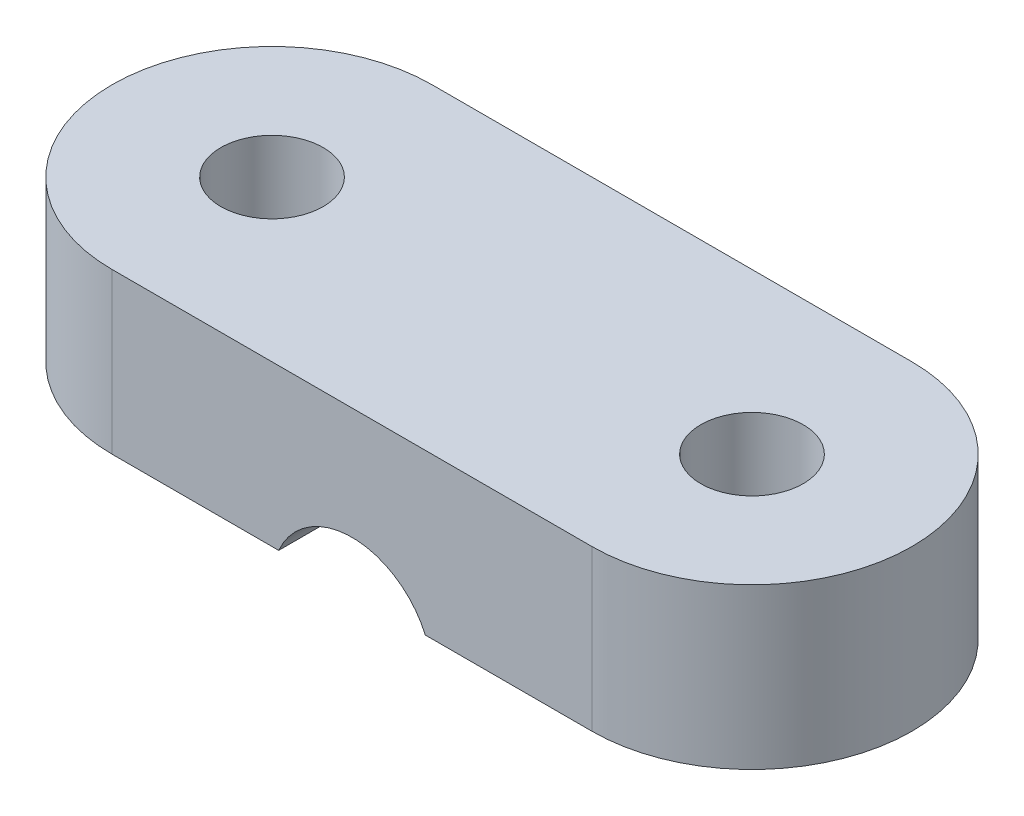
SolidWorks part; units mm, degrees
ref_plane "Front Plane" through (0, 0, 0) normal (0, 0, 1) x (1, 0, 0)
ref_plane "Top Plane" through (0, 0, 0) normal (0, 1, 0) x (1, 0, 0)
ref_plane "Right Plane" through (0, 0, 0) normal (1, 0, 0) x (0, 0, -1)
sketch "Sketch1" plane through (0, 0, 0) normal (0, 1, 0) x (1, 0, 0)
  line L0 (-7.5, 0) -> (7.5, 0) construction
  line L1 (-7.5, 5) -> (7.5, 5)
  line L2 (-7.5, -5) -> (7.5, -5)
  arc A0 (-7.5, 5) -> (-7.5, -5) centre (-7.5, 0) ccw
  arc A1 (7.5, -5) -> (7.5, 5) centre (7.5, 0) ccw
  circle A2 centre (-7.5, 0) radius 1.6
  circle A3 centre (7.5, 0) radius 1.6
  point P3 (0, 0)
  point P12 (-10, -2.9256)
  dimension "D2" = 3.2
  dimension "D1" = 15
  dimension "D3" = 10
extrude "Boss-Extrude1" add sketch "Sketch1" along normal blind 5
sketch "Sketch2" plane through (0, 0, 5) normal (0, 0, 1) x (1, 0, 0)
  line L0 (0, 0) -> (0, -1) construction
  circle A0 centre (0, -1) radius 2.5
  dimension "D1" = 5
  dimension "D2" = 1
extrude "Cut-Extrude1" cut sketch "Sketch2" against normal through all
